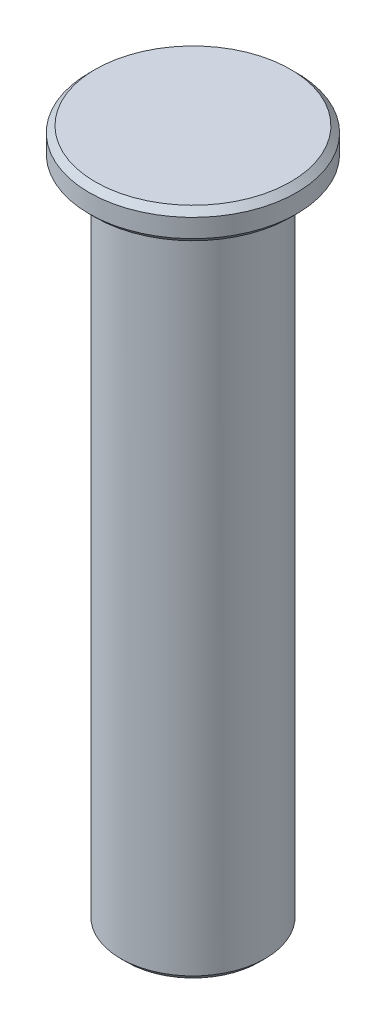
SolidWorks part; units mm, degrees
material "Plain Carbon Steel"
ref_plane "Front Plane" through (0, 0, 0) normal (0, 0, 1) x (1, 0, 0)
ref_plane "Top Plane" through (0, 0, 0) normal (0, 1, 0) x (1, 0, 0)
ref_plane "Right Plane" through (0, 0, 0) normal (1, 0, 0) x (0, 0, -1)
sketch "Sketch1" plane through (0, 0, 0) normal (0, 1, 0) x (1, 0, 0)
  circle A0 centre (0, 0) radius 4.7
  dimension "D1" = 9.4
extrude "Boss-Extrude1" add sketch "Sketch1" along normal blind 45
sketch "Sketch2" plane through (0, 45, 0) normal (0, 1, 0) x (1, 0, 0)
  circle A0 centre (0, 0) radius 6.75
  dimension "D1" = 13.5
extrude "Boss-Extrude2" add sketch "Sketch2" against normal blind 2
chamfer "Chamfer1" distance 0.4 angle 45 3 edges at (0, 43, 6.75) (0, 45, 6.75) (0, 0, 4.7)
